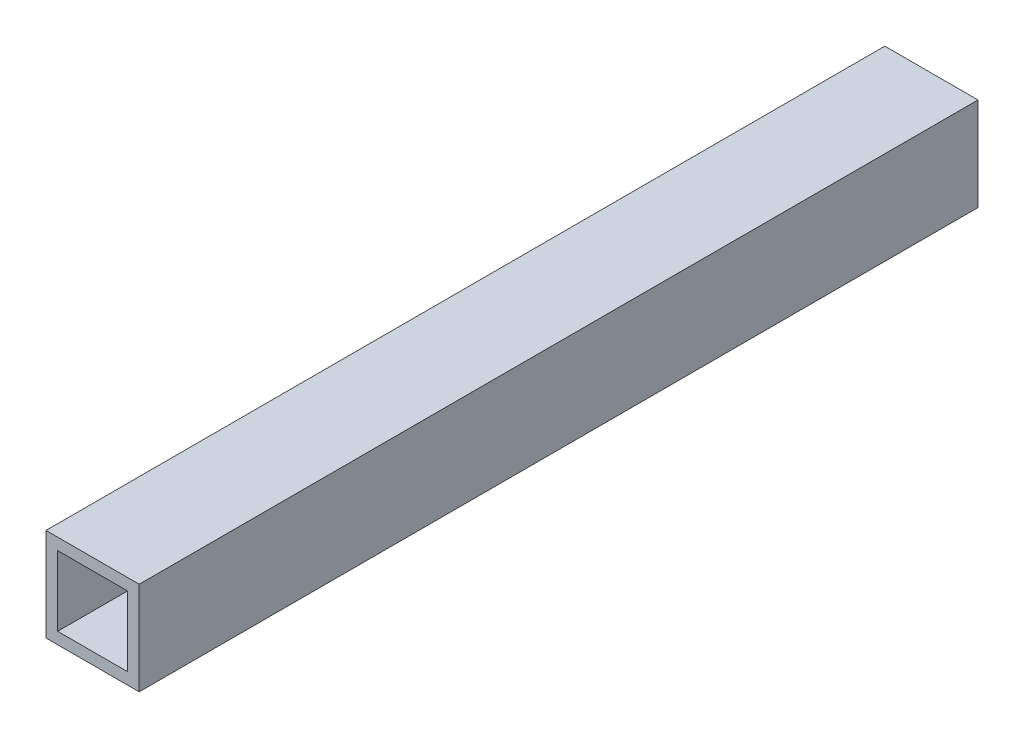
SolidWorks part; units mm, degrees
ref_plane "Front Plane" through (0, 0, 0) normal (0, 0, 1) x (1, 0, 0)
ref_plane "Top Plane" through (0, 0, 0) normal (0, 1, 0) x (1, 0, 0)
ref_plane "Right Plane" through (0, 0, 0) normal (1, 0, 0) x (0, 0, -1)
sketch "Sketch2" plane through (0, 0, 0) normal (0, 0, 1) x (1, 0, 0)
  line L0 (-69.4913, -5.7277) -> (-94.8913, -5.7277)
  line L1 (-94.8913, -5.7277) -> (-94.8913, 19.6723)
  line L2 (-94.8913, 19.6723) -> (-94.8913, 16.4973)
  line L3 (-94.8913, 19.6723) -> (-69.4913, 19.6723)
  line L4 (-94.8913, 19.6723) -> (-94.8913, -5.7277)
  line L5 (-94.8913, -5.7277) -> (-69.4913, -5.7277)
  line L6 (-69.4913, 19.6723) -> (-69.4913, -5.7277)
  line L8 (-69.4913, -5.7277) -> (-72.6663, -5.7277)
  line L11 (-91.7163, 16.4973) -> (-72.6663, 16.4973)
  line L12 (-91.7163, 16.4973) -> (-91.7163, -2.5527)
  line L13 (-91.7163, -2.5527) -> (-72.6663, -2.5527)
  line L14 (-72.6663, 16.4973) -> (-72.6663, -2.5527)
  point P8 (0, 0)
  point P11 (0, 0)
  point P12 (0, 0)
extrude "Boss-Extrude1" add sketch "Sketch2" along normal blind 228.6 contours L6 L3 L1 L5 L0 L11 L14 L13 L12
